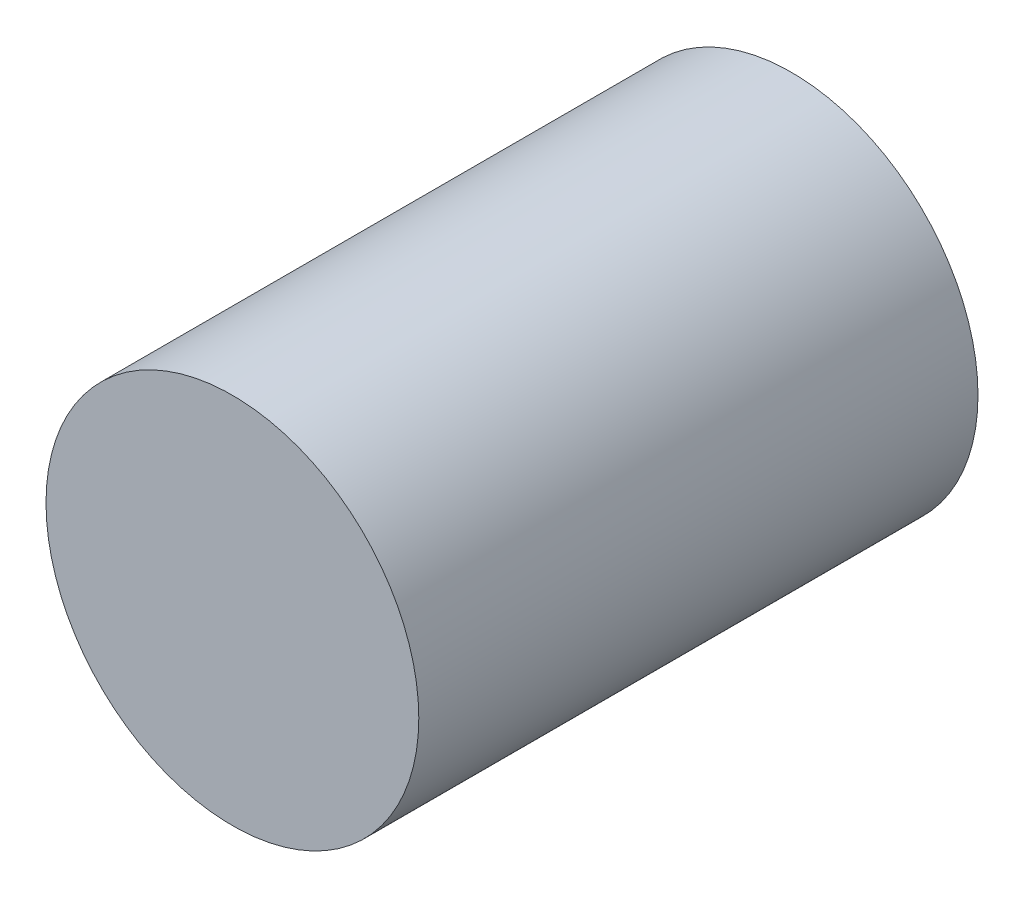
SolidWorks part; units mm, degrees
ref_plane "Front Plane" through (0, 0, 0) normal (0, 0, 1) x (1, 0, 0)
ref_plane "Top Plane" through (0, 0, 0) normal (0, 1, 0) x (1, 0, 0)
ref_plane "Right Plane" through (0, 0, 0) normal (1, 0, 0) x (0, 0, -1)
sketch "Sketch1" plane through (0, 0, 0) normal (0, 0, 1) x (1, 0, 0)
  circle A0 centre (0, 0) radius 152.4
  dimension "D1" = 304.8
extrude "Boss-Extrude1" add sketch "Sketch1" along normal blind 457.2
